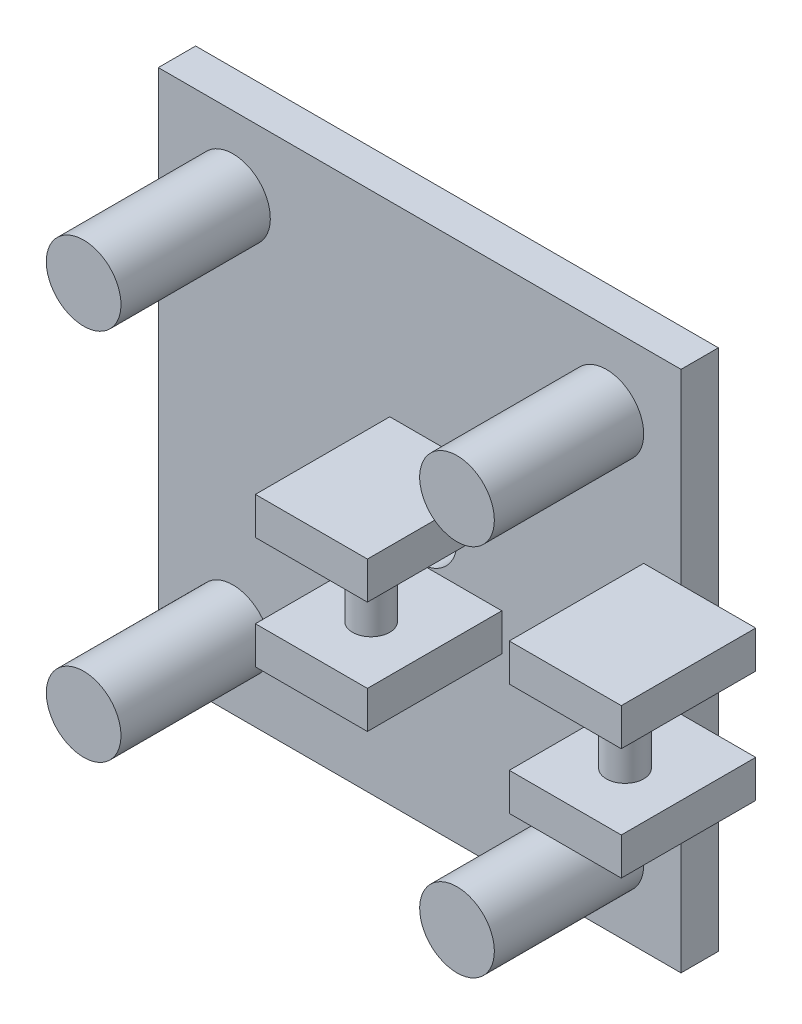
SolidWorks part; units mm, degrees
ref_plane "Front Plane" through (0, 0, 0) normal (0, 0, 1) x (1, 0, 0)
ref_plane "Top Plane" through (0, 0, 0) normal (0, 1, 0) x (1, 0, 0)
ref_plane "Right Plane" through (0, 0, 0) normal (1, 0, 0) x (0, 0, -1)
sketch "Sketch1" plane through (0, 0, 0) normal (0, 0, 1) x (1, 0, 0)
  line L1 (-35, 35) -> (35, 35)
  line L2 (-35, 35) -> (-35, -35)
  line L3 (-35, -35) -> (35, -35)
  line L4 (35, 35) -> (35, -35)
  line L5 (-35, 35) -> (35, -35) construction
  line L6 (-35, -35) -> (35, 35) construction
  circle A0 centre (0, 0) radius 5
  point P0 (0, 0)
  dimension "D1" = 70
  dimension "D3" = 10
  dimension "D2" = 70
extrude "Boss-Extrude1" add sketch "Sketch1" along normal blind 5
sketch "Sketch2" plane through (0, 0, 5) normal (0, 0, 1) x (1, 0, 0)
  line L0 (35, -35) -> (35, 35) construction
  line L1 (35, 35) -> (-35, 35) construction
  circle A0 centre (25, 25) radius 5
  dimension "D1" = 10
  dimension "D2" = 10
  dimension "D3" = 10
extrude "Boss-Extrude2" add sketch "Sketch2" along normal blind 20
pattern_circular "CirPattern1" count 4 over 360 about axis through (0, 0, 0) along (0, 0, 1) of "Boss-Extrude2"
sketch "Sketch3" plane through (0, 0, 5) normal (0, 0, 1) x (1, 0, 0)
  line L0 (35, -35) -> (35, 35) construction
  line L1 (-4, -10) -> (11, -10)
  line L2 (-4, -10) -> (-4, -5)
  line L3 (-4, -5) -> (11, -5)
  line L4 (11, -10) -> (11, -5)
  line L5 (-4, -10) -> (11, -5) construction
  line L6 (-4, -5) -> (11, -10) construction
  line L7 (-4, 5) -> (11, 5)
  line L8 (-4, 5) -> (-4, 10)
  line L9 (-4, 10) -> (11, 10)
  line L10 (11, 5) -> (11, 10)
  line L11 (-4, 5) -> (11, 10) construction
  line L12 (-4, 10) -> (11, 5) construction
  line L13 (30, -10) -> (45, -10)
  line L14 (30, -10) -> (30, -5)
  line L15 (30, -5) -> (45, -5)
  line L16 (45, -10) -> (45, -5)
  line L17 (30, -10) -> (45, -5) construction
  line L18 (30, -5) -> (45, -10) construction
  line L19 (30, 5) -> (45, 5)
  line L20 (30, 5) -> (30, 10)
  line L21 (30, 10) -> (45, 10)
  line L22 (45, 5) -> (45, 10)
  line L23 (30, 5) -> (45, 10) construction
  line L24 (30, 10) -> (45, 5) construction
  point P0 (3.5, -7.5)
  point P5 (3.5, 7.5)
  point P10 (37.5, -7.5)
  point P16 (37.5, 7.5)
  dimension "D1" = 15
  dimension "D2" = 15
  dimension "D3" = 5
  dimension "D4" = 3.5
  dimension "D5" = 3.5
  dimension "D6" = 5
  dimension "D7" = 5
  dimension "D8" = 5
  dimension "D9" = 5
  dimension "D10" = 5
  dimension "D11" = 5
  dimension "D12" = 5
  dimension "D13" = 15
  dimension "D14" = 15
  dimension "D15" = 5
  dimension "D16" = 10
extrude "Boss-Extrude3" add sketch "Sketch3" along normal blind 18
sketch "Sketch4" plane through (0, 10, 0) normal (0, 1, 0) x (1, 0, 0)
  line L0 (11, -23) -> (-4, -23) construction
  line L1 (45, -23) -> (30, -23) construction
  line L2 (11, -23) -> (11, -5) construction
  line L3 (45, -23) -> (45, -5) construction
  circle A0 centre (3.5, -15) radius 2.5
  circle A1 centre (37.5, -15) radius 2.5
  point P8 (11, -14)
  dimension "D1" = 5
  dimension "D2" = 8
  dimension "D3" = 7.5
  dimension "D4" = 8
  dimension "D5" = 7.5
  dimension "D6" = 5
extrude "Boss-Extrude4" add sketch "Sketch4" against normal up to surface (20 mm away) up to face at (3.5, -10, 14)
